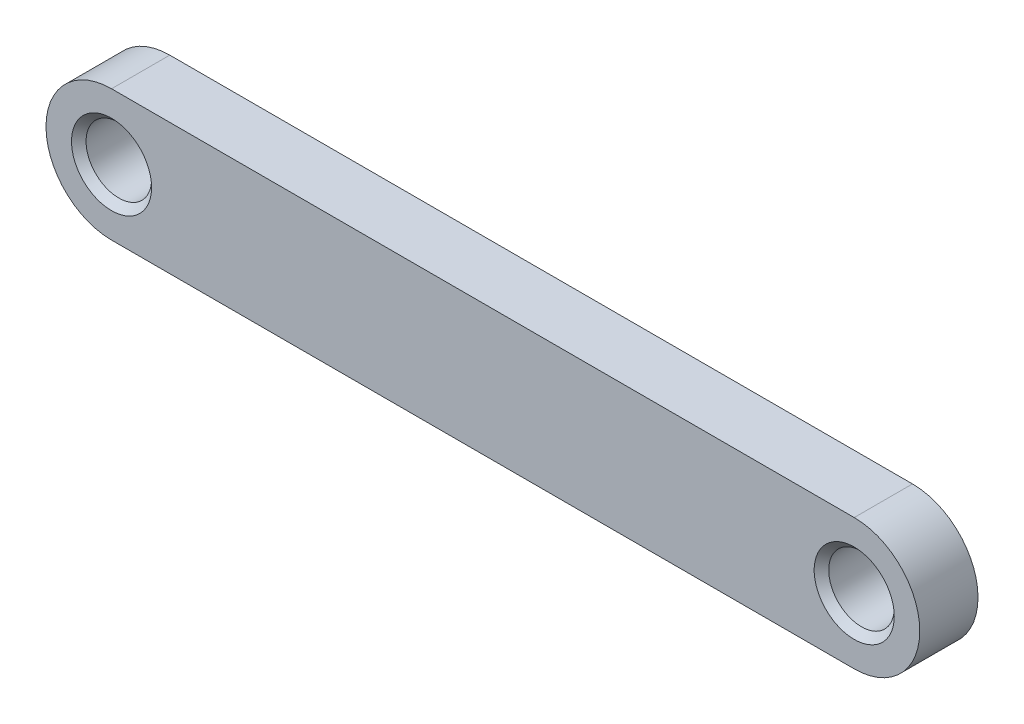
SolidWorks part; units mm, degrees
ref_plane "Piano frontale" through (0, 0, 0) normal (0, 0, 1) x (1, 0, 0)
ref_plane "Piano superiore" through (0, 0, 0) normal (0, 1, 0) x (1, 0, 0)
ref_plane "Piano destro" through (0, 0, 0) normal (1, 0, 0) x (0, 0, -1)
sketch "Sketch1" plane through (0, 0, 0) normal (0, 0, 1) x (1, 0, 0)
  line L0 (0, 0) -> (102, 0) construction
  line L1 (0, 9) -> (102, 9)
  line L2 (0, -9) -> (102, -9)
  arc A0 (0, 9) -> (0, -9) centre (0, 0) ccw
  arc A1 (102, -9) -> (102, 9) centre (102, 0) ccw
  circle A2 centre (0, 0) radius 4.5
  circle A3 centre (102, 0) radius 4.5
  point P3 (51, 0)
  dimension "D2" = 18
  dimension "D3" = 9
  dimension "D4" = 9
  dimension "D1" = 102
extrude "Boss-Extrude1" add sketch "Sketch1" along normal blind 8
chamfer "Chamfer1" distance 1 angle 45 2 edges at (106.5, 0, 8) (4.5, 0, 8)
